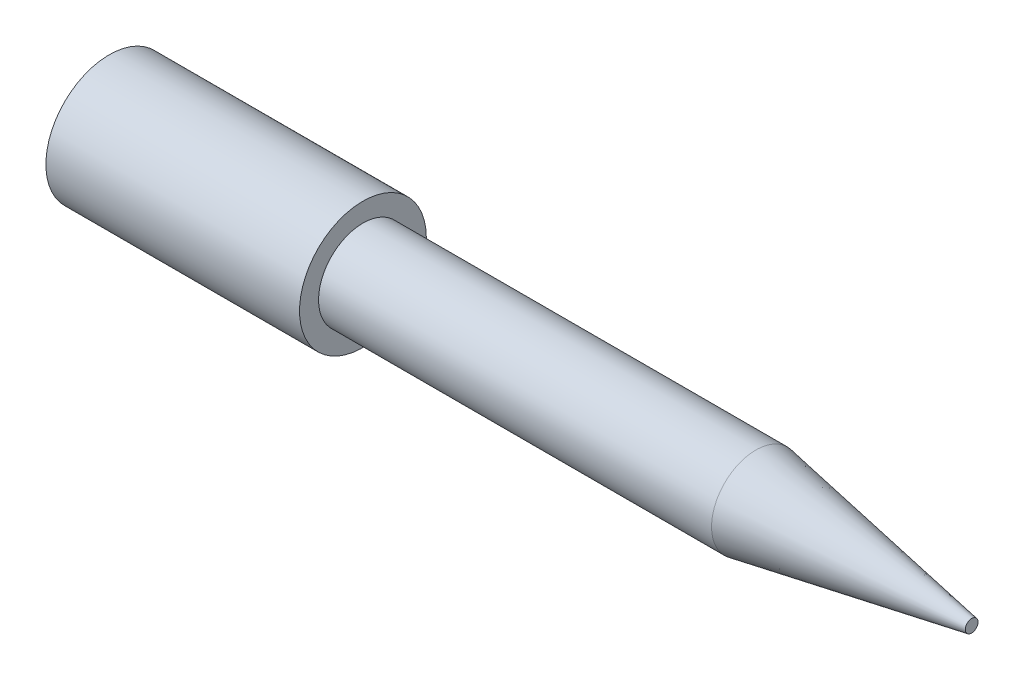
SolidWorks part; units mm, degrees
material "Plain Carbon Steel"
ref_plane "Front" through (0, 0, 0) normal (0, 0, 1) x (1, 0, 0)
ref_plane "Top" through (0, 0, 0) normal (0, 1, 0) x (1, 0, 0)
ref_plane "Right" through (0, 0, 0) normal (1, 0, 0) x (0, 0, -1)
sketch "Sketch1" plane through (0, 0, 0) normal (1, 0, 0) x (0, 0, -1)
  circle A0 centre (0, 0) radius 2.5
  dimension "D1" = 5
extrude "Boss-Extrude1" add sketch "Sketch1" along normal blind 10
sketch "Sketch2" plane through (10, 0, 0) normal (1, 0, 0) x (0, 0, -1)
  circle A0 centre (0, 0) radius 1.75
  dimension "D1" = 3.5
extrude "Boss-Extrude2" add sketch "Sketch2" along normal blind 24
chamfer "Chamfer1" distance 1.5 angle 80 1 edges at (34, 0, -1.75)
